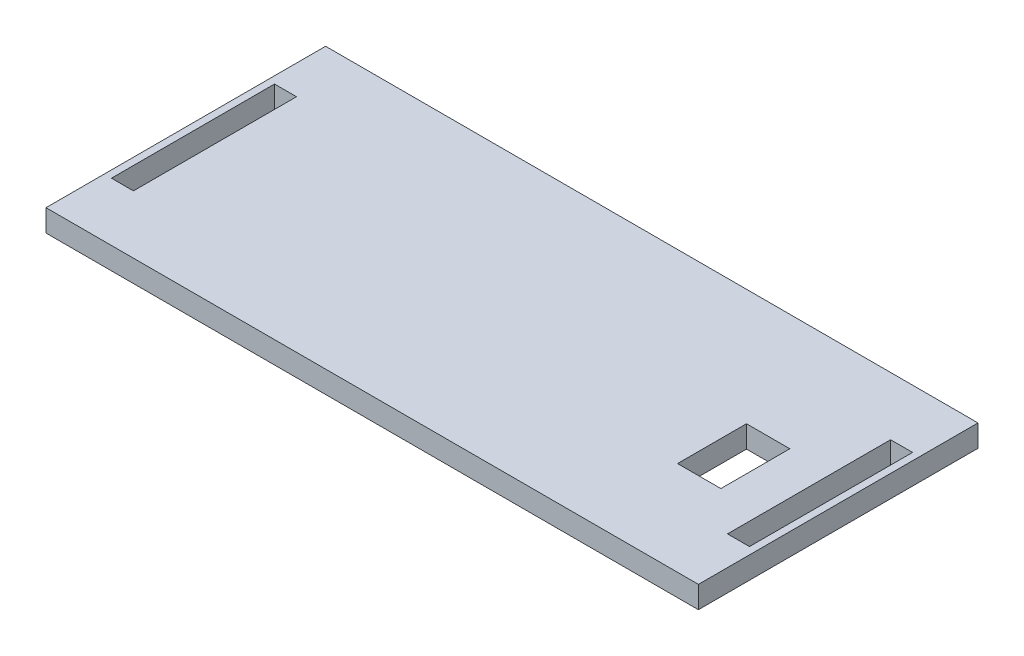
SolidWorks part; units mm, degrees
ref_plane "Front Plane" through (0, 0, 0) normal (0, 0, 1) x (1, 0, 0)
ref_plane "Top Plane" through (0, 0, 0) normal (0, 1, 0) x (1, 0, 0)
ref_plane "Right Plane" through (0, 0, 0) normal (1, 0, 0) x (0, 0, -1)
sketch "Sketch1" plane through (0, 0, 0) normal (0, 1, 0) x (1, 0, 0)
  line L1 (0, 0) -> (177.8, 0)
  line L2 (0, 0) -> (0, -76.2)
  line L3 (0, -76.2) -> (177.8, -76.2)
  line L4 (177.8, 0) -> (177.8, -76.2)
  line L5 (1.9548, -15.875) -> (7.9492, -15.875)
  line L6 (1.9548, -15.875) -> (1.9548, -60.325)
  line L7 (1.9548, -60.325) -> (7.9492, -60.325)
  line L8 (7.9492, -15.875) -> (7.9492, -60.325)
  line L9 (175.8452, -15.875) -> (169.8508, -15.875)
  line L10 (175.8452, -15.875) -> (175.8452, -60.325)
  line L11 (175.8452, -60.325) -> (169.8508, -60.325)
  line L12 (169.8508, -15.875) -> (169.8508, -60.325)
  line L13 (158.2557, -31.7373) -> (146.4447, -31.7373)
  line L14 (158.2557, -31.7373) -> (158.2557, -50.5333)
  line L15 (158.2557, -50.5333) -> (146.4447, -50.5333)
  line L16 (146.4447, -31.7373) -> (146.4447, -50.5333)
  point P9 (1.9548, -38.1)
  point P10 (0, -38.1)
  point P15 (175.8452, -38.1)
  point P16 (177.8, -38.1)
  dimension "D1" = 177.8
  dimension "D2" = 76.2
  dimension "D3" = 44.45
  dimension "D4" = 5.9944
  dimension "D5" = 1.9548
  dimension "D6" = 5.9944
  dimension "D7" = 44.45
  dimension "D8" = 1.9548
  dimension "D9" = 11.811
  dimension "D10" = 18.796
  dimension "D11" = 11.5951
  dimension "D12" = 25.6667
extrude "Boss-Extrude1" add sketch "Sketch1" along normal blind 5.9944
